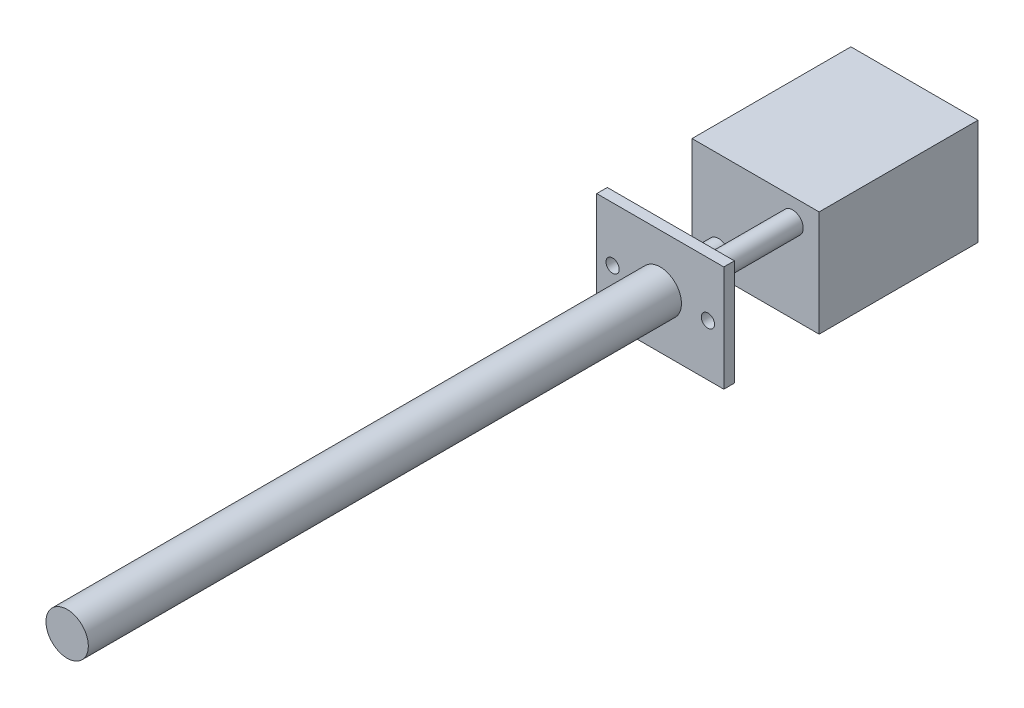
SolidWorks part; units mm, degrees
ref_plane "Front Plane" through (0, 0, 0) normal (0, 0, 1) x (1, 0, 0)
ref_plane "Top Plane" through (0, 0, 0) normal (0, 1, 0) x (1, 0, 0)
ref_plane "Right Plane" through (0, 0, 0) normal (1, 0, 0) x (0, 0, -1)
sketch "Sketch2" plane through (0, 0, 0) normal (0, 0, 1) x (1, 0, 0)
  line L1 (-6, -5) -> (6, -5)
  line L2 (-6, -5) -> (-6, 5)
  line L3 (-6, 5) -> (6, 5)
  line L4 (6, -5) -> (6, 5)
  line L5 (-6, -5) -> (6, 5) construction
  line L6 (-6, 5) -> (6, -5) construction
  point P0 (0, 0)
  dimension "D1" = 10
  dimension "D2" = 12
extrude "Boss-Extrude1" add sketch "Sketch2" against normal blind 15
ref_plane "Plane1" through (0, 0, 9) normal (0, 0, 1) x (1, 0, 0)
sketch "Sketch3" plane through (0, 0, 9) normal (0, 0, 1) x (1, 0, 0)
  line L0 (6, 5) -> (-6, 5) construction
  line L1 (-6, -5) -> (6, -5)
  line L2 (-6, -5) -> (-6, 5)
  line L3 (-6, 5) -> (6, 5)
  line L4 (6, -5) -> (6, 5)
  line L5 (-6, -5) -> (6, 5) construction
  line L6 (-6, 5) -> (6, -5) construction
  line L7 (-6, 5) -> (-6, -5) construction
  point P0 (0, 0)
extrude "Boss-Extrude2" add sketch "Sketch3" against normal blind 1 separate body
sketch "Sketch4" plane through (0, 0, 9) normal (0, 0, 1) x (1, 0, 0)
  circle A0 centre (0, 0) radius 2
  dimension "D1" = 4
extrude "Boss-Extrude3" add sketch "Sketch4" along normal blind 56
sketch "Sketch5" plane through (0, 0, 8) normal (0, 0, -1) x (-1, 0, 0)
  line L0 (-6, 5) -> (6, -5) construction
  line L1 (0, 5) -> (0, 0) construction
  line L2 (-6, 5) -> (6, 5) construction
  circle A0 centre (-3.5, 2.9167) radius 1
  circle A1 centre (3.5, -2.9167) radius 1
  dimension "D1" = 2
  dimension "D2" = 3.5
  dimension "D3" = 3.5
extrude "Boss-Extrude4" add sketch "Sketch5" along normal up to next
hole_wizard "M1.6 Tapped Hole1" positions "Sketch8" profile "Sketch9" tap size "M1.6" standard "ISO"
sketch "Sketch8" plane through (0, 0, 9) normal (0, 0, 1) x (1, 0, 0)
  line L0 (-4.5, -0.1395) -> (4.5, -0.1395) construction
  line L2 (0, 0) -> (0, 5) construction
  line L3 (6, 5) -> (-6, 5) construction
  point P0 (-4.5, -0.1395)
  point P2 (4.5, -0.1395)
  dimension "D1" = 9
sketch "Sketch9" plane through (-4.5, -0.1395, 9) normal (1, 0, 0) x (0, -1, 0)
  line L0 (0, 0) -> (0, 4.6255)
  line L1 (0, 4.6255) -> (0.625, 4.25)
  line L2 (0.625, 4.25) -> (0.625, 0)
  line L5 (0.625, 0) -> (0, 0)
  line L10 (0, 4.6255) -> (-0.625, 4.25) construction
  line L11 (0, -6.35) -> (0, 107.95) construction
  dimension "Tap Drill Dia." = 1.25
  dimension "Tap Drill Depth" = 4.25
  dimension "Drill Angle" = 118
cosmetic thread "Hole Thread1" parameters "D1"=3.2, "D2"=1.6
cosmetic thread "Hole Thread2" parameters "D1"=3.2, "D2"=1.6
